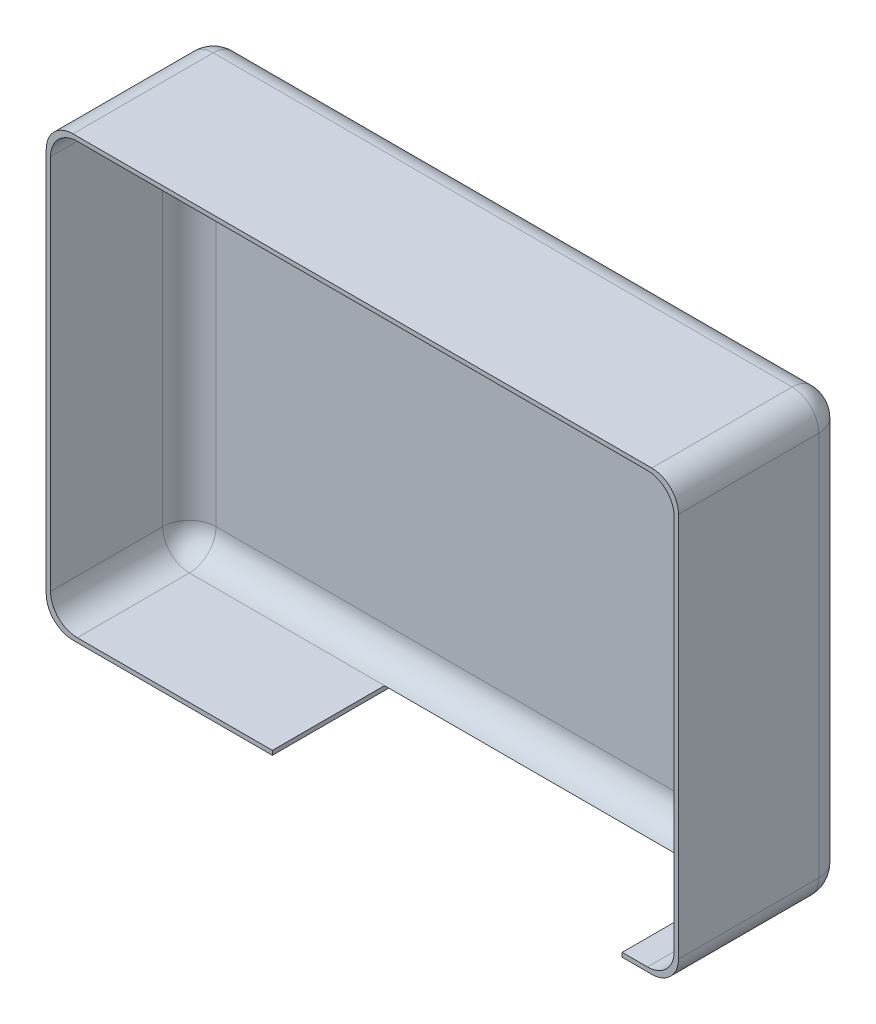
SolidWorks part; units mm, degrees
material "Custom Plastic"
ref_plane "Front Plane" through (0, 0, 0) normal (0, 0, 1) x (1, 0, 0)
ref_plane "Top Plane" through (0, 0, 0) normal (0, 1, 0) x (1, 0, 0)
ref_plane "Right Plane" through (0, 0, 0) normal (1, 0, 0) x (0, 0, -1)
sketch "Sketch1" plane through (0, 0, 0) normal (0, 0, 1) x (1, 0, 0)
  line L1 (-41.4059, 22.0562) -> (266.6961, 22.0562)
  line L2 (-55.6299, 7.8322) -> (-55.6299, -197.1458)
  line L3 (-41.4059, -211.3698) -> (266.6961, -211.3698)
  line L4 (280.9201, 7.8322) -> (280.9201, -197.1458)
  arc A0 (-41.4059, 22.0562) -> (-55.6299, 7.8322) centre (-41.4059, 7.8322) ccw
  arc A1 (-55.6299, -197.1458) -> (-41.4059, -211.3698) centre (-41.4059, -197.1458) ccw
  arc A2 (266.6961, -211.3698) -> (280.9201, -197.1458) centre (266.6961, -197.1458) ccw
  arc A3 (280.9201, 7.8322) -> (266.6961, 22.0562) centre (266.6961, 7.8322) ccw
  point P6 (-55.6299, 22.0562)
  point P9 (-55.6299, -211.3698)
  point P14 (280.9201, 22.0562)
  dimension "D3" = 14.224
  dimension "D4" = 14.224
  dimension "D1" = 336.55
  dimension "D2" = 233.426
extrude "Boss-Extrude1" add sketch "Sketch1" along normal blind 88.9
sketch "Sketch4" plane through (0, 0, 88.9) normal (0, 0, 1) x (1, 0, 0)
  line L0 (-39.1199, -209.0838) -> (264.4101, -209.0838)
  line L1 (-53.3439, -194.8598) -> (-53.3439, 5.5462)
  line L2 (-39.1199, 19.7702) -> (264.4101, 19.7702)
  line L3 (278.6341, -194.8598) -> (278.6341, 5.5462)
  line L4 (266.6961, 22.0562) -> (-41.4059, 22.0562) construction
  line L5 (-55.6299, 7.8322) -> (-55.6299, -197.1458) construction
  arc A0 (-53.3439, -194.8598) -> (-39.1199, -209.0838) centre (-39.1199, -194.8598) ccw
  arc A1 (264.4101, -209.0838) -> (278.6341, -194.8598) centre (264.4101, -194.8598) ccw
  arc A2 (278.6341, 5.5462) -> (264.4101, 19.7702) centre (264.4101, 5.5462) ccw
  arc A3 (-39.1199, 19.7702) -> (-53.3439, 5.5462) centre (-39.1199, 5.5462) ccw
  point P12 (112.6451, 19.7702)
  point P15 (112.6451, 22.0562)
  point P16 (-53.3439, -94.6568)
  point P19 (-55.6299, -94.6568)
extrude "Cut-Extrude1" cut sketch "Sketch4" against normal blind 73.914
fillet "Fillet1" radius 14.224 8 edges at (-49.1778, -204.9177, 14.986) (-53.3439, -94.6568, 14.986) (-49.1778, 15.6041, 14.986) (112.6451, 19.7702, 14.986) (274.4679, 15.6041, 14.986) (278.6341, -94.6568, 14.986) (274.4679, -204.9177, 14.986) (112.6451, -209.0838, 14.986)
fillet "Fillet2" radius 14.224 8 edges at (-55.6299, -94.6568, 0) (-51.4638, 17.8901, 0) (112.6451, 22.0562, 0) (276.7539, 17.8901, 0) (280.9201, -94.6568, 0) (276.7539, -207.2037, 0) (112.6451, -211.3698, 0) (-51.4638, -207.2037, 0)
sketch "Sketch5" plane through (0, -211.3698, 0) normal (0, -1, 0) x (-1, 0, 0)
  line L0 (41.4059, -14.224) -> (-266.6961, -14.224) construction
  line L1 (-69.8382, -14.224) -> (-245.8858, -14.224)
  line L2 (-64.7582, -19.304) -> (-64.7582, -88.9)
  line L3 (-64.7582, -88.9) -> (-250.9658, -88.9)
  line L4 (-250.9658, -19.304) -> (-250.9658, -88.9)
  line L5 (-277.5745, -88.9) -> (55.9275, -88.9) construction
  arc A0 (-245.8858, -14.224) -> (-250.9658, -19.304) centre (-245.8858, -19.304) ccw
  arc A1 (-69.8382, -14.224) -> (-64.7582, -19.304) centre (-69.8382, -19.304) cw
  point P12 (-64.7582, -14.224)
  dimension "D1" = 5.08
extrude "Cut-Extrude2" cut sketch "Sketch5" against normal blind 2.286
